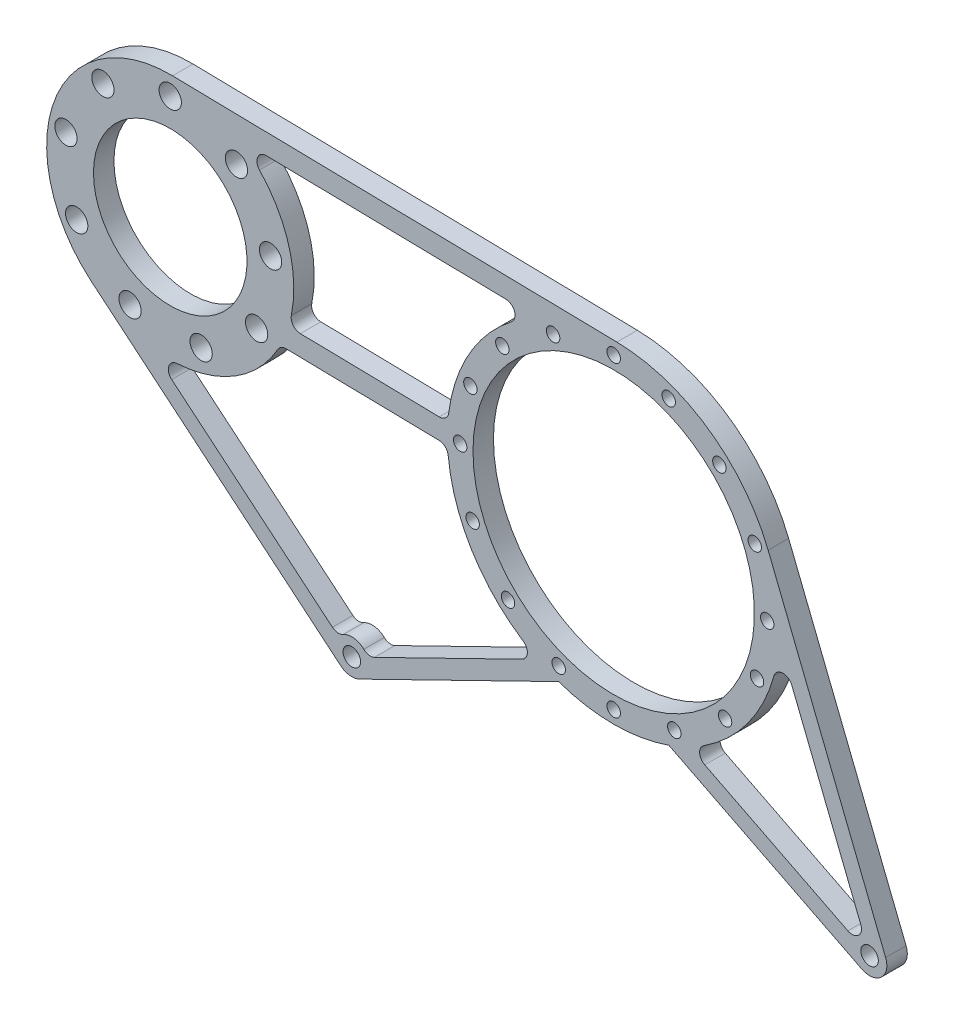
SolidWorks part; units mm, degrees
ref_plane "Front Plane" through (0, 0, 0) normal (0, 0, 1) x (1, 0, 0)
ref_plane "Top Plane" through (0, 0, 0) normal (0, 1, 0) x (1, 0, 0)
ref_plane "Right Plane" through (0, 0, 0) normal (1, 0, 0) x (0, 0, -1)
sketch "Sketch2" plane through (0, 0, 0) normal (0, 0, 1) x (1, 0, 0)
  line L0 (-114.3, 107.95) -> (-114.3, 95.25) construction
  line L1 (-308.8752, 91.6841) -> (-215.9253, 14.1066)
  line L2 (-278.5268, 172.9917) -> (-113.1247, 169.8513)
  line L3 (-13.0706, 21.4387) -> (-56.8054, 130.918)
  line L4 (-208.9705, 13.2659) -> (-134.815, 49.5352)
  line L5 (-21.9498, 13.301) -> (-93.785, 49.5352)
  circle A0 centre (-279.4, 127) radius 28.575
  circle A1 centre (-114.3, 95.25) radius 36 construction
  circle A2 centre (0, 0) radius 12.7 construction
  circle A3 centre (-228.6, 0) radius 12.7 construction
  arc A4 (-278.5268, 172.9917) -> (-308.8752, 91.6841) centre (-279.4, 127) ccw
  arc A5 (-134.815, 49.5352) -> (-93.785, 49.5352) centre (-114.3, 107.95) ccw
  circle A6 centre (-19.05, 19.05) radius 3.2639
  circle A7 centre (-211.7995, 19.05) radius 3.2639
  arc A8 (-215.9253, 14.1066) -> (-208.9705, 13.2659) centre (-211.7995, 19.05) ccw
  arc A9 (-21.9498, 13.301) -> (-13.0706, 21.4387) centre (-19.05, 19.05) ccw
  circle A10 centre (-114.3, 107.95) radius 52.3875
  arc A11 (-56.8054, 130.918) -> (-113.1247, 169.8513) centre (-114.3, 107.95) ccw
  dimension "D1" = 25.4
  dimension "D2" = 25.4
  dimension "D8" = 57.15
  dimension "D9" = 72
  dimension "D10" = 92
  dimension "D12" = 123.825
  dimension "D13" = 6.5278
  dimension "D16" = 6.5278
  dimension "D18" = 3.175
  dimension "D20" = 104.775
  dimension "D3" = 228.6
  dimension "D4" = 114.3
  dimension "D5" = 95.25
  dimension "D6" = 279.4
  dimension "D7" = 127
  dimension "D11" = 12.7
  dimension "D14" = 19.05
  dimension "D15" = 19.05
  dimension "D17" = 25.4
  dimension "D19" = 82.55
extrude "Boss-Extrude1" add sketch "Sketch2" along normal blind 7.62
sketch "Sketch3" plane through (0, 0, 7.62) normal (0, 0, 1) x (1, 0, 0)
  line L0 (-279.4, 127) -> (-279.4, 166.0004) construction
  line L1 (-114.3, 107.95) -> (-114.3, 165.1) construction
  line L2 (-114.3, 107.95) -> (-93.8193, 161.3041) construction
  line L3 (-114.3, 107.95) -> (-74.9605, 149.4051) construction
  line L4 (-114.3, 107.95) -> (-61.7911, 130.5096) construction
  line L5 (-114.3, 107.95) -> (-57.15, 107.95) construction
  line L6 (-114.3, 107.95) -> (-60.9459, 87.4693) construction
  line L7 (-114.3, 107.95) -> (-72.8449, 68.6105) construction
  line L8 (-114.3, 107.95) -> (-91.7404, 55.4411) construction
  line L9 (-114.3, 107.95) -> (-114.3, 50.8) construction
  line L10 (-114.3, 107.95) -> (-134.7807, 54.5959) construction
  line L11 (-114.3, 107.95) -> (-153.6395, 66.4949) construction
  line L12 (-114.3, 107.95) -> (-166.8089, 85.3904) construction
  line L13 (-114.3, 107.95) -> (-171.45, 107.95) construction
  line L14 (-114.3, 107.95) -> (-167.6541, 128.4307) construction
  line L15 (-114.3, 107.95) -> (-155.7551, 147.2895) construction
  line L16 (-114.3, 107.95) -> (-136.8596, 160.4589) construction
  circle A0 centre (-279.4, 127) radius 39.0004 construction
  circle A1 centre (-279.4, 166.0004) radius 4.15
  circle A2 centre (-254.7465, 156.3809) radius 4.15
  circle A3 centre (-242.0442, 133.1649) radius 4.15
  circle A4 centre (-247.2366, 107.2156) radius 4.15
  circle A5 centre (-267.8941, 90.6748) radius 4.15
  circle A6 centre (-294.3509, 91.2822) radius 4.15
  circle A7 centre (-314.2275, 108.7537) radius 4.15
  circle A8 centre (-318.2234, 134.914) radius 4.15
  circle A9 centre (-304.469, 157.5225) radius 4.15
  circle A10 centre (-114.3, 107.95) radius 57.15 construction
  circle A11 centre (-114.3, 165.1) radius 2.5
  circle A12 centre (-93.8193, 161.3041) radius 2.5
  circle A13 centre (-74.9605, 149.4051) radius 2.5
  circle A21 centre (-61.7911, 130.5096) radius 2.5
  circle A22 centre (-57.15, 107.95) radius 2.5
  circle A23 centre (-60.9459, 87.4693) radius 2.5
  circle A24 centre (-72.8449, 68.6105) radius 2.5
  circle A25 centre (-91.7404, 55.4411) radius 2.5
  circle A26 centre (-114.3, 50.8) radius 2.5
  circle A27 centre (-134.7807, 54.5959) radius 2.5
  circle A28 centre (-153.6395, 66.4949) radius 2.5
  circle A29 centre (-166.8089, 85.3904) radius 2.5
  circle A30 centre (-171.45, 107.95) radius 2.5
  circle A31 centre (-167.6541, 128.4307) radius 2.5
  circle A32 centre (-155.7551, 147.2895) radius 2.5
  circle A33 centre (-136.8596, 160.4589) radius 2.5
  point P24 (-280.288, 127.3232)
  point P48 (-114.3, 107.95)
  point P61 (-114.3, 107.95)
  dimension "D1" = 78.0009
  dimension "D2" = 8.3
  dimension "D4" = 21
  dimension "D5" = 5
  dimension "D7" = 66.75
  dimension "D6" = 43.5
  dimension "D3" = 9
extrude "Cut-Extrude1" cut sketch "Sketch3" against normal through all both and the other way through all
sketch "Sketch4" plane through (0, 0, 7.62) normal (0, 0, 1) x (1, 0, 0)
  line L0 (-278.8602, 74.9042) -> (-219.0194, 24.9601)
  line L1 (-48.0193, 91.8071) -> (-22.3039, 27.4349)
  line L2 (-308.8752, 91.6841) -> (-215.9253, 14.1066) construction
  line L3 (-148.3931, 49.9629) -> (-203.3792, 23.0694)
  line L4 (-208.9705, 13.2659) -> (-134.815, 49.5352) construction
  line L5 (-243.5726, 164.7067) -> (-154.4587, 163.0147)
  line L6 (-113.1247, 169.8513) -> (-278.5268, 172.9917) construction
  line L7 (-80.3879, 49.8896) -> (-27.12, 23.021)
  line L8 (-93.785, 49.5352) -> (-21.9498, 13.301) construction
  line L9 (-13.0706, 21.4387) -> (-56.8054, 130.918) construction
  line L10 (-230.9639, 113.6581) -> (-179.2529, 112.6763)
  line L11 (-236.2483, 106.1371) -> (-179.3262, 105.0564)
  arc A0 (-234.3202, 117.8451) -> (-239.355, 104.3639) centre (-279.4, 127) ccw construction
  arc A1 (-175.9167, 101.9055) -> (-175.7218, 115.7294) centre (-114.3, 107.95) ccw construction
  circle A2 centre (-19.05, 19.05) radius 6.4389 construction
  circle A3 centre (-211.7995, 19.05) radius 6.4389 construction
  arc A4 (-278.5268, 172.9917) -> (-308.8752, 91.6841) centre (-279.4, 127) ccw construction
  arc A5 (-246.1625, 158.8004) -> (-234.3202, 117.8451) centre (-279.4, 127) cw
  arc A6 (-152.3771, 156.769) -> (-175.7218, 115.7294) centre (-114.3, 107.95) ccw
  arc A7 (-54.6287, 91.4427) -> (-80.7099, 55.9417) centre (-114.3, 107.95) cw
  arc A8 (-154.4587, 163.0147) -> (-152.3771, 156.769) centre (-154.525, 159.5229) cw
  arc A9 (-243.5726, 164.7067) -> (-246.1625, 158.8004) centre (-243.6389, 161.2148) ccw
  arc A10 (-278.8602, 74.9042) -> (-276.8184, 81.0725) centre (-276.6224, 77.5855) cw
  arc A11 (-148.0251, 56.0292) -> (-148.3931, 49.9629) centre (-149.9276, 53.1003) cw
  arc A12 (-80.3879, 49.8896) -> (-80.7099, 55.9417) centre (-78.8151, 53.0079) cw
  arc A13 (-48.0193, 91.8071) -> (-54.6287, 91.4427) centre (-51.2626, 90.5115) ccw
  arc A14 (-27.12, 23.021) -> (-22.3039, 27.4349) centre (-25.5472, 26.1393) ccw
  arc A15 (-215.0295, 24.6201) -> (-207.3352, 23.69) centre (-211.7995, 19.05) cw
  arc A16 (-203.3792, 23.0694) -> (-207.3352, 23.69) centre (-204.9137, 26.2067) cw
  arc A17 (-219.0194, 24.9601) -> (-215.0295, 24.6201) centre (-216.7815, 27.6414) ccw
  arc A18 (-239.355, 104.3639) -> (-276.8184, 81.0725) centre (-279.4, 127) cw
  arc A19 (-175.9167, 101.9055) -> (-148.0251, 56.0292) centre (-114.3, 107.95) ccw
  arc A20 (-179.3262, 105.0564) -> (-175.9167, 101.9055) centre (-179.3925, 101.5645) cw
  arc A21 (-179.2529, 112.6763) -> (-175.7218, 115.7294) centre (-179.1866, 116.1682) ccw
  arc A22 (-230.9639, 113.6581) -> (-234.3202, 117.8451) centre (-230.8976, 117.15) cw
  arc A23 (-236.2483, 106.1371) -> (-239.355, 104.3639) centre (-236.3146, 102.6452) ccw
  point P40 (-253.319, 164.8917)
  point P43 (-286.9018, 81.6158)
  point P46 (-142.5125, 52.8391)
  point P50 (-52.5701, 103.1988)
  point P56 (-216.7994, 23.1072)
  dimension "D1" = 61.9125
  dimension "D2" = 12.8778
  dimension "D3" = 12.8778
  dimension "D9" = 3.4925
  dimension "D10" = 61.9125
  dimension "D11" = 3.4925
  dimension "D14" = 3.4925
  dimension "D4" = 6.35
  dimension "D5" = 6.35
  dimension "D6" = 7.62
  dimension "D7" = 6.35
  dimension "D8" = 6.35
  dimension "D12" = 50.8
  dimension "D13" = 7.62
extrude "Cut-Extrude2" cut sketch "Sketch4" against normal through all both and the other way through all
